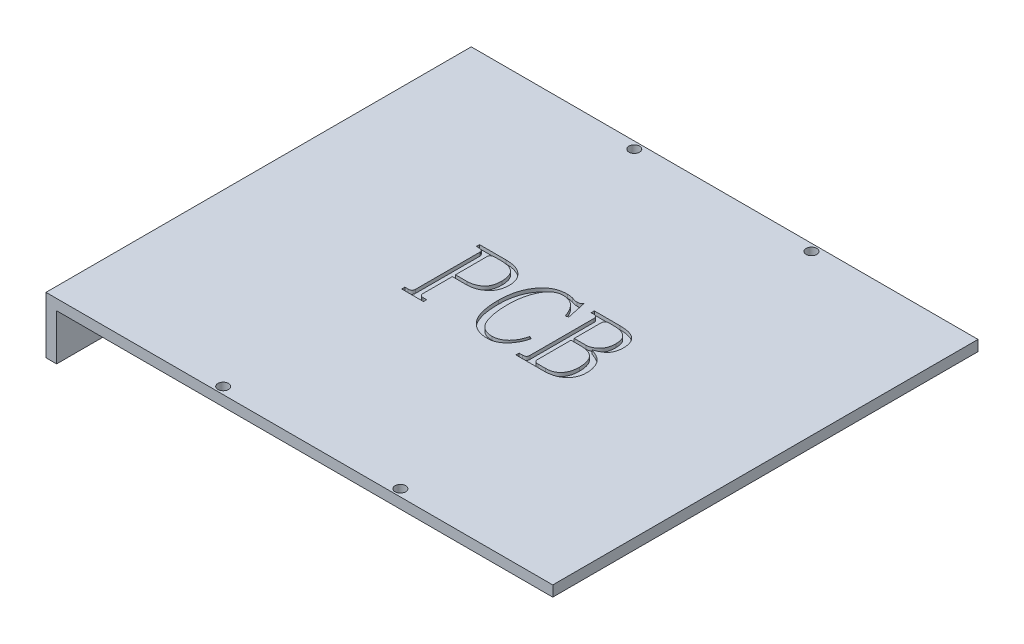
SolidWorks part; units mm, degrees
ref_plane "前视基准面" through (0, 0, 0) normal (0, 0, 1) x (1, 0, 0)
ref_plane "上视基准面" through (0, 0, 0) normal (0, 1, 0) x (1, 0, 0)
ref_plane "右视基准面" through (0, 0, 0) normal (1, 0, 0) x (0, 0, -1)
other "Configuration Table"
sketch "草图1" plane through (0, 0, 0) normal (0, 1, 0) x (1, 0, 0)
  line L1 (0, 0) -> (140, 0)
  line L2 (0, 0) -> (0, 120)
  line L3 (0, 120) -> (140, 120)
  line L4 (140, 0) -> (140, 120)
  circle A0 centre (45, 118) radius 1.5
  circle A1 centre (95, 118) radius 1.5
  circle A2 centre (95, 2) radius 1.5
  circle A3 centre (45, 2) radius 1.5
extrude "凸台-拉伸1" add sketch "草图1" along normal blind 3
sketch "草图2" plane through (0, 3, 0) normal (0, 1, 0) x (1, 0, 0)
  line L1 (0, 0) -> (-3, 0)
  line L2 (0, 0) -> (0, 120)
  line L3 (0, 120) -> (-3, 120)
  line L4 (-3, 0) -> (-3, 120)
extrude "凸台-拉伸2" add sketch "草图2" against normal blind 16
sketch "草图3" plane through (-3, 0, 0) normal (-1, 0, 0) x (0, 0, 1)
  line L0 (-67, -4.5) -> (-67, 0)
  line L3 (-120, 0) -> (0, 0) construction
  line L5 (-67, -2.25) -> (-83, -2.25)
  line L6 (-67, -2.25) -> (-67, -3.25)
  line L7 (-67, -3.25) -> (-83, -3.25)
  line L8 (-83, -2.25) -> (-83, -3.25)
  line L9 (-83, -5.5) -> (-67, -5.5)
  line L10 (-83, -5.5) -> (-83, -4.5)
  line L11 (-83, -4.5) -> (-67, -4.5)
  line L12 (-67, -5.5) -> (-67, -4.5)
extrude "切除-拉伸1" cut sketch "草图3" against normal blind 13 contours L5 L8 L7 L0
sketch "草图4" plane through (0, 0, 0) normal (1, 0, 0) x (0, 0, -1)
  line L2 (16.75, 0) -> (29.75, 0)
  line L4 (120, 0) -> (0, 0) construction
  line L5 (16.75, 0) -> (16.75, -6.8)
  line L6 (16.75, -6.8) -> (29.75, -6.8)
  line L7 (29.75, 0) -> (29.75, -6.8)
extrude "切除-拉伸2" cut sketch "草图4" against normal blind 13 contours L5 L2 L7 L6
sketch "草图5" plane through (0, 3, 0) normal (0, 1, 0) x (1, 0, 0)
  text T0 "PCB" font "宋体" height in points 72
extrude "切除-拉伸3" cut sketch "草图5" against normal blind 1
